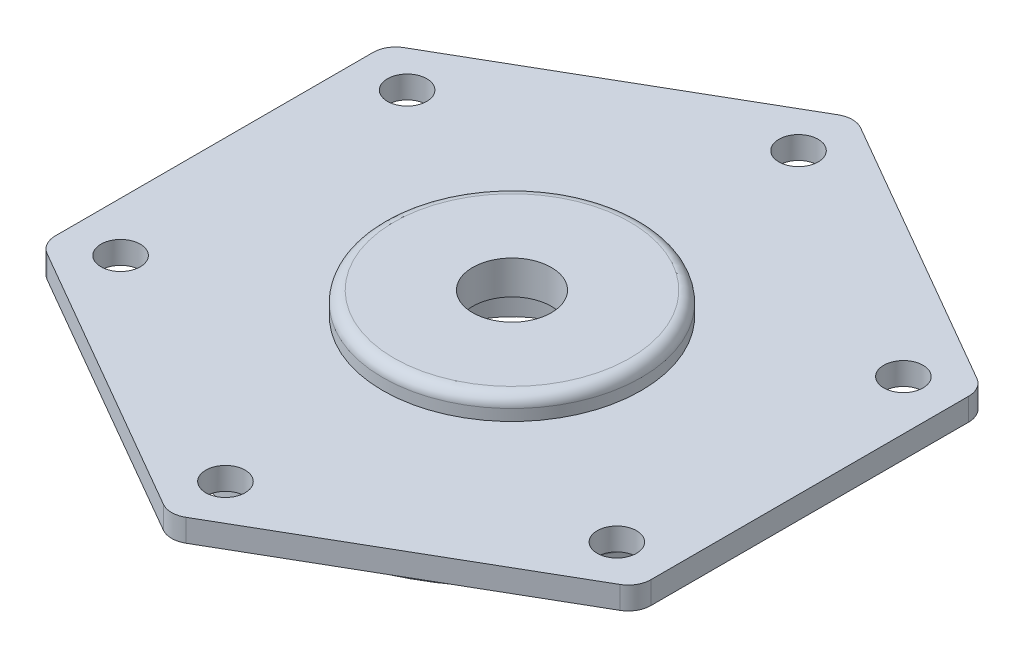
SolidWorks part; units mm, degrees
ref_plane "Front Plane" through (0, 0, 0) normal (0, 0, 1) x (1, 0, 0)
ref_plane "Top Plane" through (0, 0, 0) normal (0, 1, 0) x (1, 0, 0)
ref_plane "Right Plane" through (0, 0, 0) normal (1, 0, 0) x (0, 0, -1)
sketch "Sketch1" plane through (0, 0, 0) normal (0, 1, 0) x (1, 0, 0)
  line L1 (2, -60.0444) -> (51, -31.7543)
  line L2 (53, -28.2902) -> (53, 28.2902)
  line L3 (51, 31.7543) -> (2, 60.0444)
  line L4 (-2, 60.0444) -> (-51, 31.7543)
  line L5 (-53, 28.2902) -> (-53, -28.2902)
  line L6 (-51, -31.7543) -> (-2, -60.0444)
  circle A0 centre (0, 0) radius 53 construction
  arc A1 (-51, -31.7543) -> (-53, -28.2902) centre (-49, -28.2902) cw
  arc A2 (-51, 31.7543) -> (-53, 28.2902) centre (-49, 28.2902) ccw
  arc A3 (-2, -60.0444) -> (2, -60.0444) centre (0, -56.5803) ccw
  arc A4 (51, -31.7543) -> (53, -28.2902) centre (49, -28.2902) ccw
  arc A5 (53, 28.2902) -> (51, 31.7543) centre (49, 28.2902) ccw
  arc A6 (2, 60.0444) -> (-2, 60.0444) centre (0, 56.5803) ccw
  point P1 (0, 0)
  point P22 (0, 61.1991)
  dimension "D2" = 4
  dimension "D1" = 106
extrude "Boss-Extrude1" add sketch "Sketch1" along normal blind 4
sketch "Sketch2" plane through (0, 4, 0) normal (0, 1, 0) x (1, 0, 0)
  circle A0 centre (0, 0) radius 23
  dimension "D1" = 46
extrude "Boss-Extrude2" add sketch "Sketch2" along normal blind 4
sketch "Sketch3" plane through (0, 0, 0) normal (0, -1, 0) x (1, 0, 0)
  circle A0 centre (0, 0) radius 45
  dimension "D1" = 90
extrude "Boss-Extrude3" add sketch "Sketch3" along normal blind 6
sketch "Sketch4" plane through (0, -6, 0) normal (0, -1, 0) x (1, 0, 0)
  circle A0 centre (0, 0) radius 40
  circle A1 centre (0, 0) radius 19
  dimension "D1" = 80
  dimension "D2" = 38
extrude "Cut-Extrude1" cut sketch "Sketch4" against normal blind 6
sketch "Sketch5" plane through (0, -6, 0) normal (0, -1, 0) x (1, 0, 0)
  circle A0 centre (0, 0) radius 14
  dimension "D1" = 28
extrude "Cut-Extrude2" cut sketch "Sketch5" against normal blind 8
sketch "Sketch6" plane through (0, 2, 0) normal (0, -1, 0) x (1, 0, 0)
  circle A0 centre (0, 0) radius 7
  dimension "D1" = 14
extrude "Cut-Extrude3" cut sketch "Sketch6" against normal through all
fillet "Fillet1" radius 2 3 edges at (0, 8, 23) (0, -6, -19) (0, 0, -45)
sketch "Sketch7" plane through (0, 4, 0) normal (0, 1, 0) x (1, 0, 0)
  circle A0 centre (0, 0) radius 51 construction
  circle A1 centre (0, 51) radius 3.5
  circle A2 centre (44.1673, 25.5) radius 3.5
  circle A3 centre (44.1673, -25.5) radius 3.5
  circle A4 centre (0, -51) radius 3.5
  circle A5 centre (-44.1673, -25.5) radius 3.5
  circle A6 centre (-44.1673, 25.5) radius 3.5
  point P18 (0, 0)
  dimension "D1" = 102
  dimension "D2" = 7
  dimension "D3" = 6
extrude "Cut-Extrude4" cut sketch "Sketch7" against normal through all
